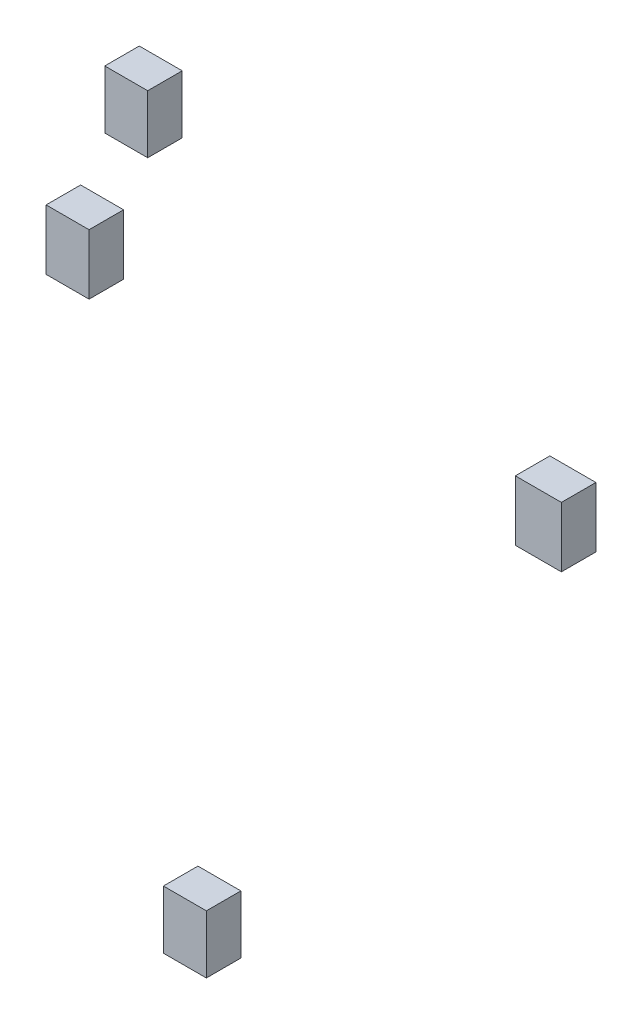
SolidWorks part; units mm, degrees
ref_plane "Front Plane" through (0, 0, 0) normal (0, 0, 1) x (1, 0, 0)
ref_plane "Top Plane" through (0, 0, 0) normal (0, 1, 0) x (1, 0, 0)
ref_plane "Right Plane" through (0, 0, 0) normal (1, 0, 0) x (0, 0, -1)
sketch "Sketch1" plane through (0, 0, 0) normal (0, 0, 1) x (1, 0, 0)
  line L0 (-7.6555, 77.7714) -> (-16.9755, 77.7714) construction
  line L1 (-16.8255, 77.6214) -> (-7.8055, 77.6214)
  line L2 (-16.8255, 77.6214) -> (-16.8255, 65.42)
  line L3 (-16.8255, 65.42) -> (-7.8055, 65.42)
  line L4 (-7.8055, 77.6214) -> (-7.8055, 65.42)
  line L5 (-7.6555, 77.7714) -> (-7.6555, 65.27) construction
  line L6 (-7.6555, 65.27) -> (-16.9755, 65.27) construction
  line L7 (-16.9755, 65.27) -> (-16.9755, 77.7714) construction
  line L8 (-4.6555, -65.25) -> (4.6645, -65.25) construction
  line L9 (-29.1455, 46.18) -> (-20.1255, 46.18)
  line L10 (-29.1455, 46.18) -> (-29.1455, 33.54)
  line L11 (-29.1455, 33.54) -> (-20.1255, 33.54)
  line L12 (-20.1255, 46.18) -> (-20.1255, 33.54)
  line L13 (69.4145, 46.18) -> (79.0868, 46.18)
  line L14 (69.4145, 46.18) -> (69.4145, 33.54)
  line L15 (69.4145, 33.54) -> (79.0868, 33.54)
  line L16 (79.0868, 46.18) -> (79.0868, 33.54)
  line L17 (-4.5055, -65.4) -> (4.5145, -65.4)
  line L18 (-4.5055, -65.4) -> (-4.5055, -77.6214)
  line L19 (-4.5055, -77.6214) -> (4.5145, -77.6214)
  line L20 (4.5145, -65.4) -> (4.5145, -77.6214)
  line L21 (4.6645, -65.25) -> (4.6645, -77.7714) construction
  line L22 (-4.6555, -77.7714) -> (4.6645, -77.7714) construction
  line L23 (-4.6555, -77.7714) -> (-4.6555, -65.25) construction
  line L24 (69.2645, 46.33) -> (79.2368, 46.33) construction
  line L25 (79.2368, 33.39) -> (79.2368, 46.33) construction
  line L26 (79.2368, 33.39) -> (69.2645, 33.39) construction
  line L27 (69.2645, 33.39) -> (69.2645, 46.33) construction
  line L28 (-29.2955, 46.33) -> (-19.9755, 46.33) construction
  line L29 (-19.9755, 46.33) -> (-19.9755, 33.39) construction
  line L30 (-19.9755, 33.39) -> (-29.2955, 33.39) construction
  line L31 (-29.2955, 33.39) -> (-29.2955, 46.33) construction
  dimension "D1" = 0.15
  dimension "D2" = 0.15
  dimension "D3" = 0.15
  dimension "D4" = 0.15
  dimension "D5" = 0.15
  dimension "D6" = 0.15
  dimension "D7" = 0.15
  dimension "D8" = 0.15
  dimension "D9" = 0.15
  dimension "D10" = 0.15
  dimension "D11" = 0.15
  dimension "D12" = 0.15
  dimension "D13" = 0.15
  dimension "D14" = 0.15
  dimension "D15" = 0.15
  dimension "D16" = 0.15
extrude "Boss-Extrude1" add sketch "Sketch1" along normal blind 7.25
shell "Shell1" thickness 0.5
shell "Shell2" thickness 0.5
shell "Shell3" thickness 0.5
shell "Shell4" thickness 0.5
equation "\"D4@Sketch1\"=\"D1@Sketch1\""
equation "\"D2@Sketch1\"=\"D1@Sketch1\""
equation "\"D3@Sketch1\"=\"D1@Sketch1\""
equation "\"D6@Sketch1\"=\"D5@Sketch1\""
equation "\"D7@Sketch1\"=\"D5@Sketch1\""
equation "\"D8@Sketch1\"=\"D5@Sketch1\""
equation "\"D10@Sketch1\"=\"D9@Sketch1\""
equation "\"D11@Sketch1\"=\"D9@Sketch1\""
equation "\"D12@Sketch1\"=\"D9@Sketch1\""
equation "\"D14@Sketch1\"=\"D13@Sketch1\""
equation "\"D15@Sketch1\"=\"D13@Sketch1\""
equation "\"D16@Sketch1\"=\"D13@Sketch1\""
